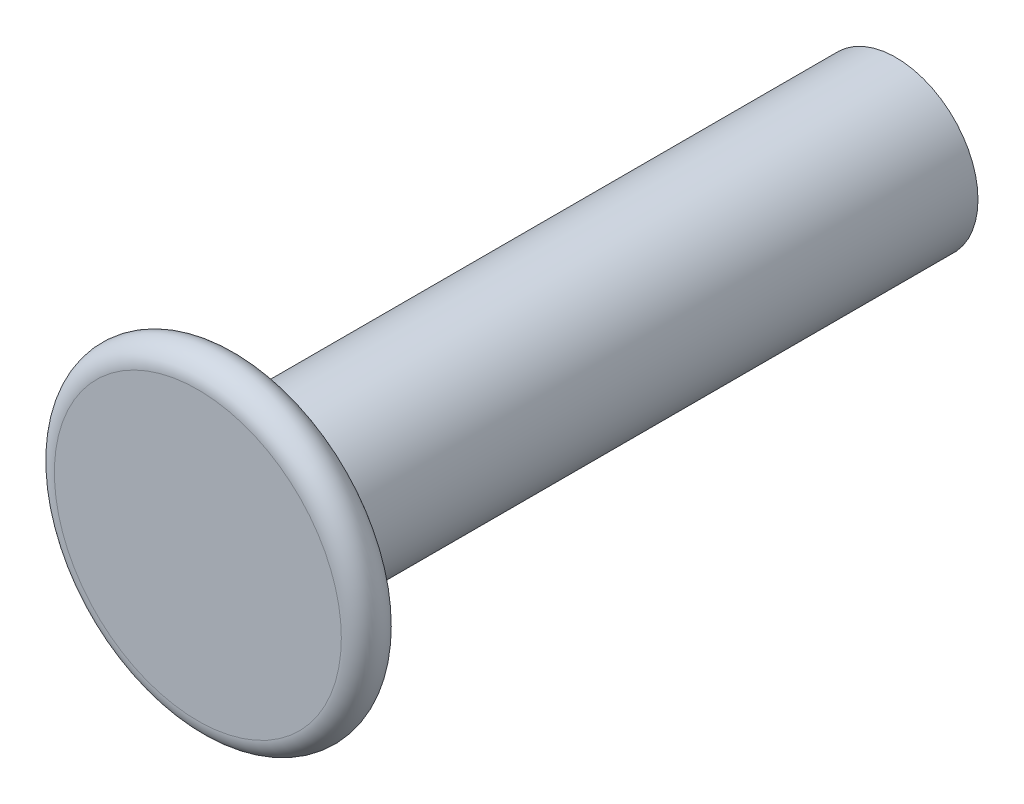
SolidWorks part; units mm, degrees
ref_plane "Front Plane" through (0, 0, 0) normal (0, 0, 1) x (1, 0, 0)
ref_plane "Top Plane" through (0, 0, 0) normal (0, 1, 0) x (1, 0, 0)
ref_plane "Right Plane" through (0, 0, 0) normal (1, 0, 0) x (0, 0, -1)
sketch "BaseBodySke" plane through (0, 0, 0) normal (0, 1, 0) x (1, 0, 0)
  line L0 (0, 0) -> (-5.5499, 0)
  line L1 (0, 0) -> (0, 54.1082) construction
  line L2 (0, 0) -> (0, 27.0002)
  line L3 (0, 27.0002) -> (-3.175, 27.0002)
  line L4 (-3.175, 1.6002) -> (-3.175, 27.0002)
  line L5 (-6.35, 27.0002) -> (-6.35, 1.6002) construction
  line L6 (-6.35, 0) -> (-6.35, 1.6002) construction
  line L8 (-5.5499, 1.6002) -> (-3.175, 1.6002)
  arc A0 (-5.5499, 1.6002) -> (-5.5499, 0) centre (-5.5499, 0.8001) ccw
  dimension "Diameter" = 6.35
  dimension "Head_Diameter" = 12.7
  dimension "Length" = 25.4
  dimension "Head_Depth" = 1.6002
revolve "BaseBody" add sketch "BaseBodySke" angle 360 about L1
